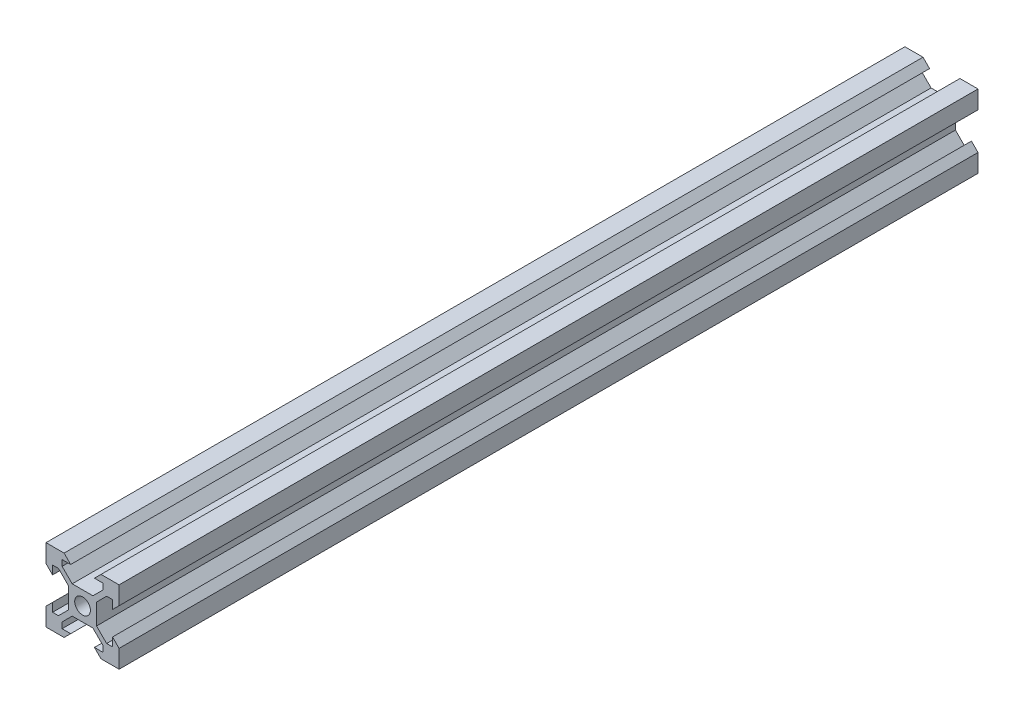
SolidWorks part; units mm, degrees
ref_plane "Alzado" through (0, 0, 0) normal (0, 0, 1) x (1, 0, 0)
ref_plane "Planta" through (0, 0, 0) normal (0, 1, 0) x (1, 0, 0)
ref_plane "Vista lateral" through (0, 0, 0) normal (1, 0, 0) x (0, 0, -1)
sketch "Croquis1" plane through (0, 0, 0) normal (0, 0, 1) x (1, 0, 0)
  line L0 (0, 0) -> (0, -20) construction
  line L2 (0, 0) -> (0, -0.5674)
  line L5 (6.175, -7.1649) -> (6.175, -12.8351)
  line L6 (7.1649, -13.825) -> (12.8351, -13.825)
  line L7 (13.825, -7.1649) -> (13.825, -12.8351)
  line L8 (7.1649, -6.175) -> (12.8351, -6.175)
  line L9 (6.175, -13.825) -> (13.825, -13.825) construction
  line L10 (13.825, -6.175) -> (13.825, -13.825) construction
  line L12 (10, -10) -> (32.1172, -10) construction
  line L13 (13.25, -18.2) -> (15.05, -20)
  line L14 (20, -20) -> (15.6, -20)
  line L15 (20, -20) -> (20, -15.6)
  line L16 (18.2, -15.6) -> (16.5899, -15.6)
  line L32 (15.6, -18.2) -> (15.6, -16.5899)
  line L33 (10, -10) -> (10, -23.2493) construction
  line L34 (4.4, -18.2) -> (4.4, -16.5899)
  line L35 (7.1649, -13.825) -> (4.4, -16.5899)
  line L36 (15.6, -18.2) -> (13.25, -18.2)
  line L38 (15.6, -20) -> (15.05, -20)
  line L40 (15.05, -20) -> (20, -20)
  line L41 (0, -20) -> (20, -20) construction
  line L42 (6.175, -12.8351) -> (3.4101, -15.6)
  line L43 (18.2, -13.25) -> (20, -15.05)
  line L44 (20, -20) -> (18.2, -20)
  line L45 (20, -20) -> (20, -15.05)
  line L48 (20, -15.05) -> (20, -20)
  line L49 (20, 0) -> (20, -20) construction
  line L50 (18.2, -15.6) -> (18.2, -13.25)
  line L51 (12.8351, -13.825) -> (15.6, -16.5899)
  line L52 (13.825, -12.8351) -> (16.5899, -15.6)
  line L53 (1.8, -15.6) -> (3.4101, -15.6)
  line L54 (1.8, -15.6) -> (1.8, -13.25)
  line L55 (1.8, -13.25) -> (0, -15.05)
  line L56 (0, 0) -> (20, 0) construction
  line L57 (0, -20) -> (0, -15.6)
  line L58 (0, -15.6) -> (0, -15.05)
  line L59 (0, -20) -> (4.4, -20)
  line L60 (0, -20) -> (4.95, -20)
  line L61 (6.75, -18.2) -> (4.95, -20)
  line L62 (4.4, -18.2) -> (6.75, -18.2)
  line L63 (1.8, -4.4) -> (3.4101, -4.4)
  line L64 (6.175, -7.1649) -> (3.4101, -4.4)
  line L65 (7.1649, -6.175) -> (4.4, -3.4101)
  line L66 (4.4, -1.8) -> (4.4, -3.4101)
  line L67 (4.4, -1.8) -> (6.75, -1.8)
  line L68 (6.75, -1.8) -> (4.95, 0)
  line L69 (0, 0) -> (4.4, 0)
  line L70 (4.4, 0) -> (4.95, 0)
  line L71 (0, 0) -> (0, -4.4)
  line L72 (0, 0) -> (0, -4.95)
  line L73 (1.8, -6.75) -> (0, -4.95)
  line L74 (1.8, -4.4) -> (1.8, -6.75)
  line L75 (15.6, -1.8) -> (15.6, -3.4101)
  line L76 (12.8351, -6.175) -> (15.6, -3.4101)
  line L77 (13.825, -7.1649) -> (16.5899, -4.4)
  line L78 (18.2, -4.4) -> (16.5899, -4.4)
  line L79 (18.2, -4.4) -> (18.2, -6.75)
  line L80 (18.2, -6.75) -> (20, -4.95)
  line L81 (20, 0) -> (20, -4.4)
  line L82 (20, -4.4) -> (20, -4.95)
  line L83 (20, 0) -> (15.6, 0)
  line L84 (20, 0) -> (15.05, 0)
  line L85 (13.25, -1.8) -> (15.05, 0)
  line L86 (15.6, -1.8) -> (13.25, -1.8)
  line L87 (6.175, -6.175) -> (13.825, -6.175) construction
  line L88 (6.175, -6.175) -> (6.175, -13.825) construction
  circle A0 centre (10, -10) radius 2.15
  point P69 (10, -10)
  dimension "D3" = 4.3
  dimension "D2" = 4
  dimension "D11" = 4.4
  dimension "D15" = 4.4
  dimension "D16" = 6.75
extrude "BoschBase" add sketch "Croquis1" along normal blind 235 contours L86 L75 L76 L8 L65 L66 L67 L68 L70 L69 L2 L71 L72 L73 L74 L63 L64 L5 L42 L53 L54 L55 L58 L57 L59 L60 L61 L62 L34 L35 L6 L51 L32 L36 L13 L38 L40 L14 L15 L45 L43 L50 L16 L52 L7 L77 L78 L79 L80 L82 L81
